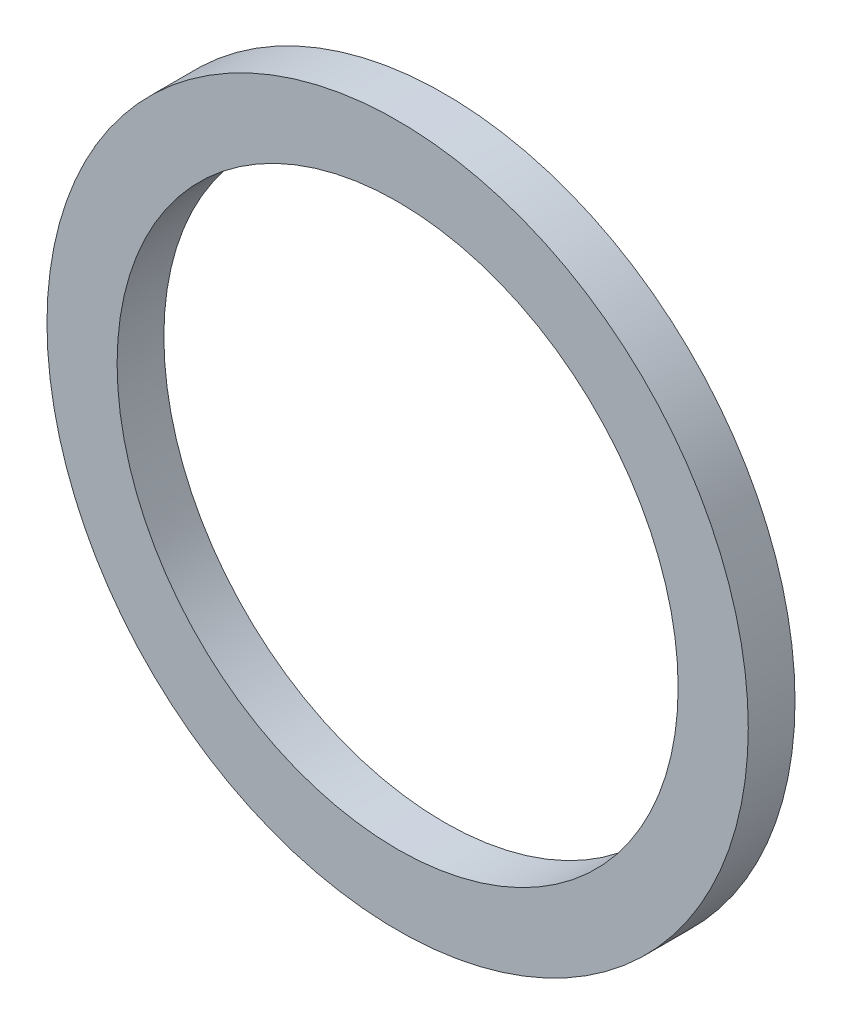
SolidWorks part; units mm, degrees
ref_plane "Alzado" through (0, 0, 0) normal (0, 0, 1) x (1, 0, 0)
ref_plane "Planta" through (0, 0, 0) normal (0, 1, 0) x (1, 0, 0)
ref_plane "Vista lateral" through (0, 0, 0) normal (1, 0, 0) x (0, 0, -1)
sketch "Croquis1" plane through (0, 0, 0) normal (0, 0, 1) x (1, 0, 0)
  circle A0 centre (0, 0) radius 7.5
  circle A1 centre (0, 0) radius 6
  dimension "D1" = 15
  dimension "D2" = 12
extrude "Saliente-Extruir1" add sketch "Croquis1" along normal blind 1
